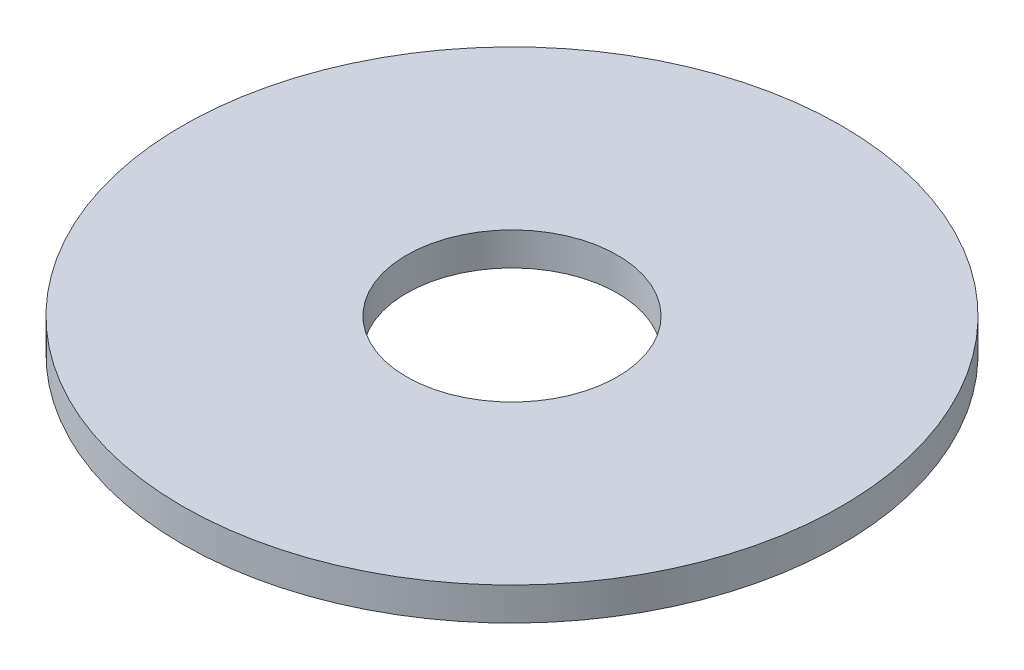
SolidWorks part; units mm, degrees
ref_plane "Ebene vorne" through (0, 0, 0) normal (0, 0, 1) x (1, 0, 0)
ref_plane "Ebene oben" through (0, 0, 0) normal (0, 1, 0) x (1, 0, 0)
ref_plane "Ebene rechts" through (0, 0, 0) normal (1, 0, 0) x (0, 0, -1)
sketch "Skizze1" plane through (0, 0, 0) normal (0, 1, 0) x (1, 0, 0)
  circle A0 centre (0, 0) radius 1.6
  circle A1 centre (0, 0) radius 5
  dimension "D1" = 10
  dimension "D2" = 3.2
extrude "Aufsatz-Linear austragen1" add sketch "Skizze1" along normal blind 0.5
